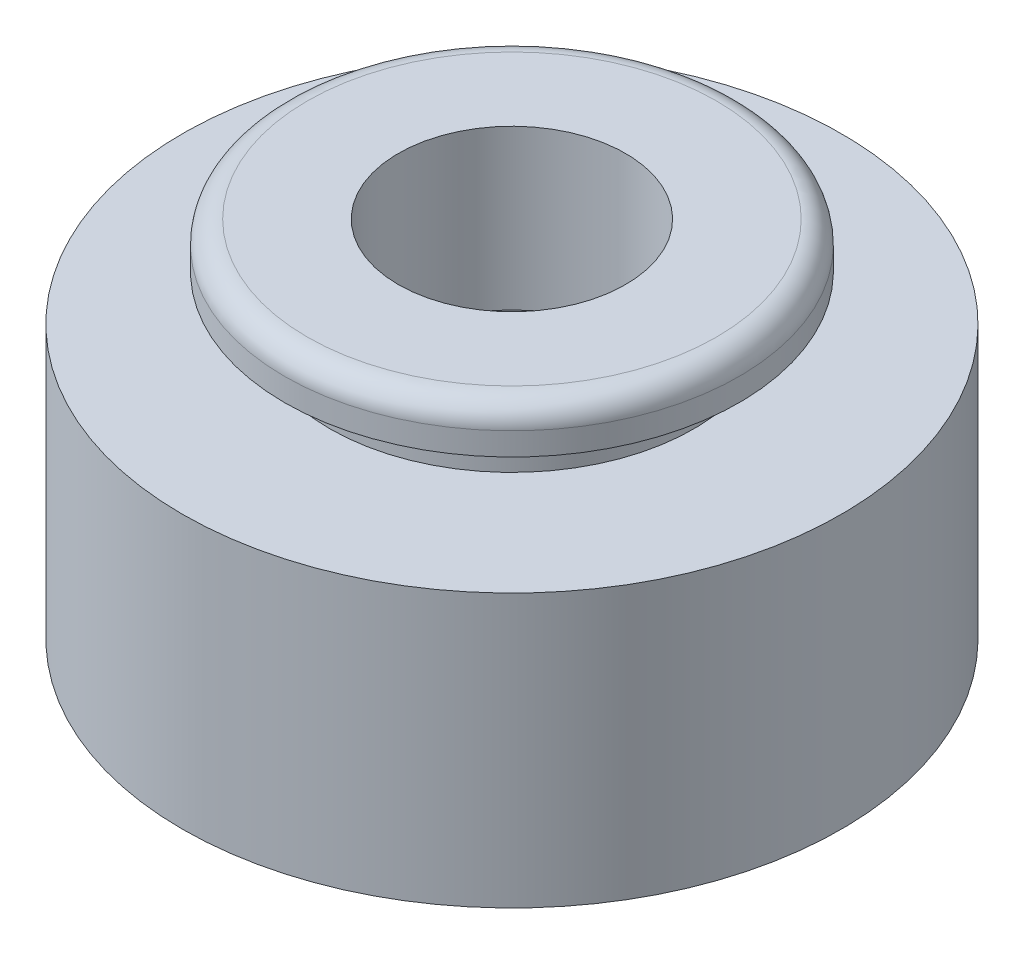
SolidWorks part; units mm, degrees
ref_plane "Спереди" through (0, 0, 0) normal (0, 0, 1) x (1, 0, 0)
ref_plane "Сверху" through (0, 0, 0) normal (0, 1, 0) x (1, 0, 0)
ref_plane "Справа" through (0, 0, 0) normal (1, 0, 0) x (0, 0, -1)
sketch "Эскиз1" plane through (0, 0, 0) normal (0, 1, 0) x (1, 0, 0)
  circle A0 centre (0, 0) radius 14.5
  circle A1 centre (0, 0) radius 7.5
  dimension "D1" = 29
  dimension "D2" = 15
extrude "Бобышка-Вытянуть1" add sketch "Эскиз1" along normal blind 12
sketch "Эскиз2" plane through (0, 12, 0) normal (0, 1, 0) x (1, 0, 0)
  circle A0 centre (0, 0) radius 8
  circle A1 centre (0, 0) radius 5
  dimension "D1" = 16
  dimension "D2" = 10
extrude "Бобышка-Вытянуть2" add sketch "Эскиз2" along normal blind 2 and the other way blind 3
sketch "Эскиз3" plane through (0, 14, 0) normal (0, 1, 0) x (1, 0, 0)
  circle A0 centre (0, 0) radius 10
  circle A1 centre (0, 0) radius 5 construction
  circle A2 centre (0, 0) radius 5
  dimension "D1" = 20
extrude "Бобышка-Вытянуть3" add sketch "Эскиз3" along normal blind 2
fillet "Скругление1" radius 1 1 edges at (0, 16, 10)
